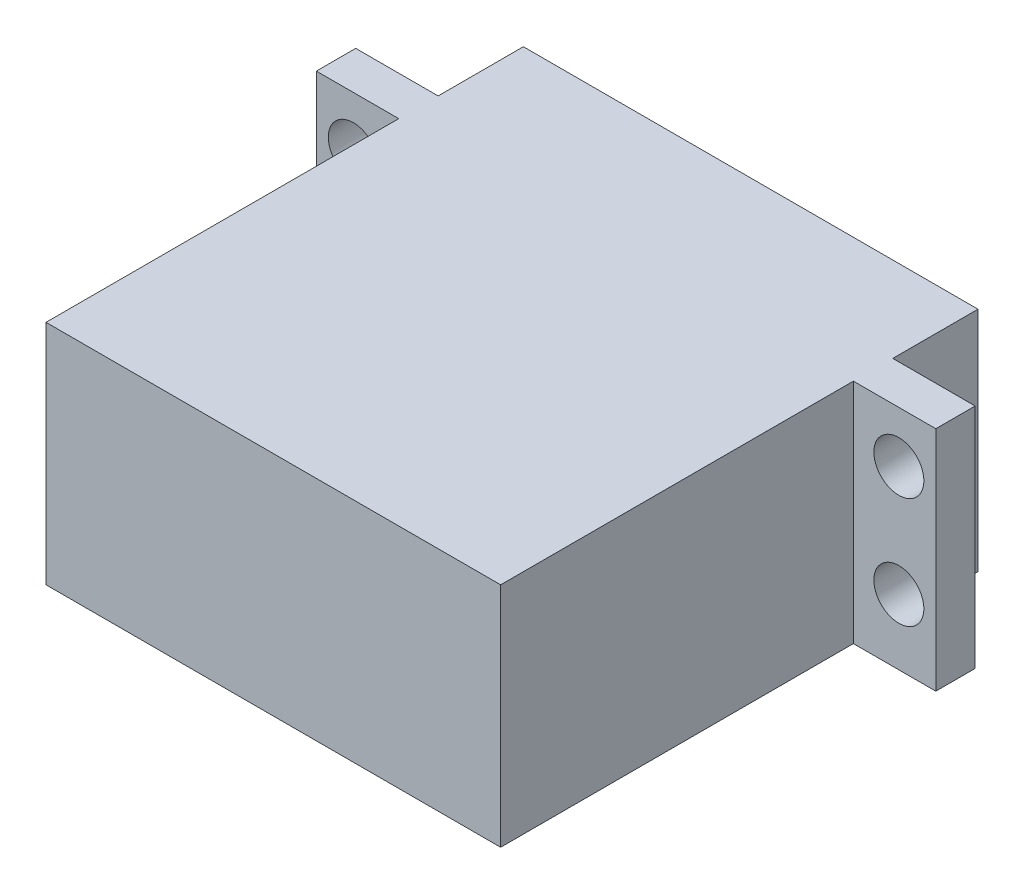
SolidWorks part; units mm, degrees
ref_plane "Спереди" through (0, 0, 0) normal (0, 0, 1) x (1, 0, 0)
ref_plane "Сверху" through (0, 0, 0) normal (0, 1, 0) x (1, 0, 0)
ref_plane "Справа" through (0, 0, 0) normal (1, 0, 0) x (0, 0, -1)
sketch "Эскиз1" plane through (0, 0, 0) normal (0, 1, 0) x (1, 0, 0)
  line L1 (-20, 21) -> (20, 21)
  line L2 (-20, 21) -> (-20, -21)
  line L3 (-20, -21) -> (20, -21)
  line L4 (20, 21) -> (20, -21)
  line L5 (-20, 21) -> (20, -21) construction
  line L6 (-20, -21) -> (20, 21) construction
  point P0 (0, 0)
  dimension "D1" = 42
  dimension "D2" = 40
extrude "Бобышка-Вытянуть1" add sketch "Эскиз1" along normal blind 20
sketch "Эскиз2" plane through (20, 0, 0) normal (1, 0, 0) x (0, 0, -1)
  line L0 (21, 20) -> (21, 0) construction
  line L1 (10.0367, 20) -> (13.5, 20)
  line L2 (10.0367, 20) -> (10.0367, 0)
  line L3 (10.0367, 0) -> (13.5, 0)
  line L4 (13.5, 20) -> (13.5, 0)
  line L5 (-21, 0) -> (21, 0) construction
  dimension "D1" = 7.5
  dimension "D2" = 20
  dimension "D3" = 0
extrude "Бобышка-Вытянуть2" add sketch "Эскиз2" along normal blind 7.25
sketch "Эскиз3" plane through (0, 0, -13.5) normal (0, 0, -1) x (-1, 0, 0)
  line L0 (-27.25, 20) -> (-20, 20) construction
  line L2 (-20, 20) -> (-20, 0) construction
  line L3 (-20, 0) -> (-20, 20) construction
  circle A0 centre (-24, 15.5) radius 2.2
  circle A1 centre (-24, 5.75) radius 2.2
  dimension "D1" = 4.4
  dimension "D3" = 4.4
  dimension "D2" = 4.5
  dimension "D4" = 14.25
  dimension "D5" = 4
  dimension "D6" = 4
extrude "Вырез-Вытянуть1" cut sketch "Эскиз3" against normal blind 7.25
ref_plane "Плоскость1" through (0, 0, 0) normal (-1, 0, 0) x (0, 0, 1)
mirror "Зеркальное отражение2" about plane through (0, 0, 0) normal (-1, 0, 0) of "Вырез-Вытянуть1", "Бобышка-Вытянуть2"
sketch "Эскиз4" plane through (0, 0, -21) normal (0, 0, -1) x (-1, 0, 0)
  line L0 (20, 0) -> (20, 20) construction
  line L1 (-20, 0) -> (20, 0) construction
  circle A0 centre (10, 10) radius 3
  dimension "D3" = 6
  dimension "D1" = 10
  dimension "D2" = 10
extrude "Бобышка-Вытянуть3" add sketch "Эскиз4" along normal blind 5
sketch "Эскиз5" plane through (0, 0, -26) normal (0, 0, -1) x (-1, 0, 0)
  circle A0 centre (10, 10) radius 1.5
  dimension "D1" = 3
extrude "Вырез-Вытянуть2" cut sketch "Эскиз5" against normal blind 5
